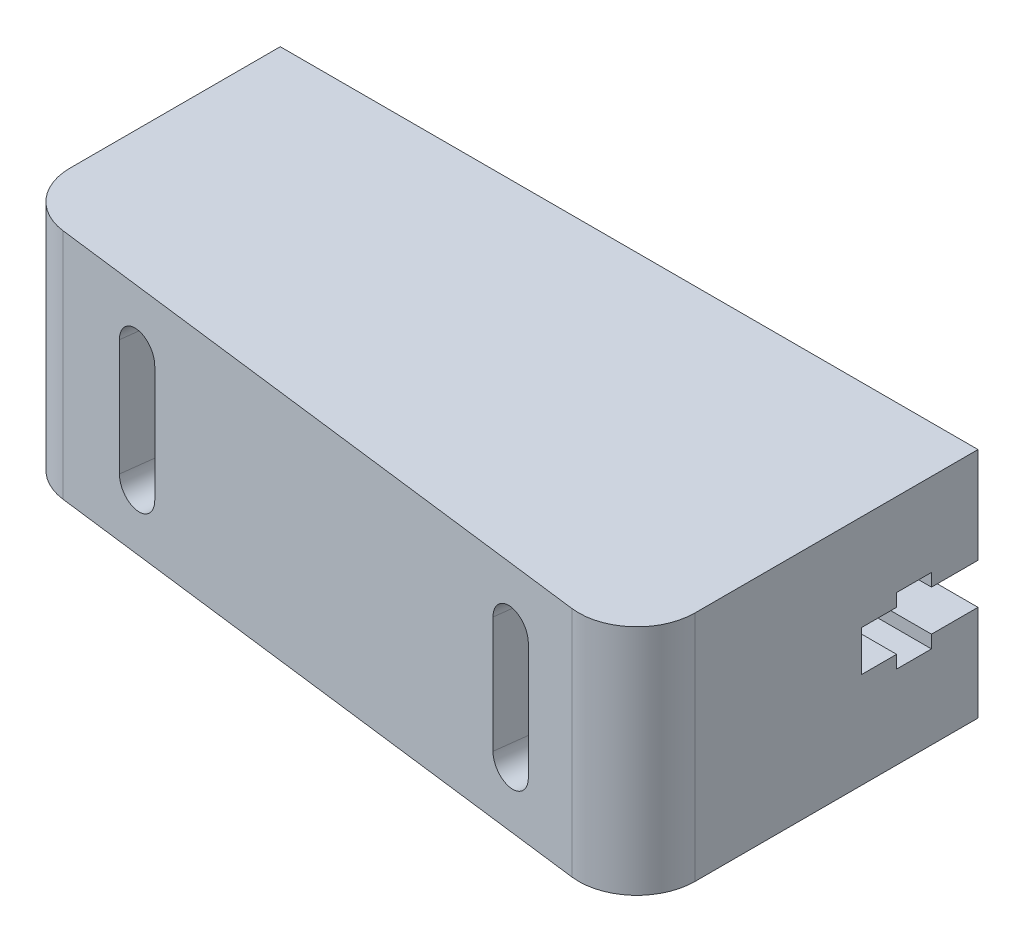
SolidWorks part; units mm, degrees
ref_plane "Front Plane" through (0, 0, 0) normal (0, 0, 1) x (1, 0, 0)
ref_plane "Top Plane" through (0, 0, 0) normal (0, 1, 0) x (1, 0, 0)
ref_plane "Right Plane" through (0, 0, 0) normal (1, 0, 0) x (0, 0, -1)
sketch "Sketch1" plane through (0, 0, 0) normal (0, 0, 1) x (1, 0, 0)
  line L1 (-30, 10) -> (30, 10)
  line L2 (-30, 10) -> (-30, -10)
  line L3 (-30, -10) -> (30, -10)
  line L4 (30, 10) -> (30, -10)
  line L5 (-30, 10) -> (30, -10) construction
  line L6 (-30, -10) -> (30, 10) construction
  point P0 (0, 0)
  dimension "D1" = 60
  dimension "D2" = 20
extrude "Boss-Extrude1" add sketch "Sketch1" along normal blind 30
sketch "Sketch2" plane through (0, 10, 0) normal (0, 1, 0) x (1, 0, 0)
  line L0 (-30, -30) -> (30, -30)
  line L1 (30, -30) -> (-30, -22.5)
  line L2 (-30, -30) -> (-30, 0) construction
  line L3 (-30, -22.5) -> (-30, -30)
  dimension "D1" = 7.5
extrude "Cut-Extrude1" cut sketch "Sketch2" against normal through all
sketch "Sketch3" plane through (0, 10, 0) normal (0, 1, 0) x (1, 0, 0)
  line L16 (-25, 0) -> (25, 0)
  line L19 (25, 0) -> (25, -24.3361)
  line L20 (25, -24.3361) -> (-25, -18.0861)
  line L21 (-25, -18.0861) -> (-25, 0)
  line L22 (25, 0) -> (25, -24.3361)
  line L23 (25, -24.3361) -> (-25, -18.0861)
  line L24 (-25, -18.0861) -> (-25, 0)
  dimension "D1" = 5
extrude "Cut-Extrude2" cut sketch "Sketch3" against normal through all from offset 4 offset against normal yes
sketch "Sketch4" plane through (-30, 0, 0) normal (-1, 0, 0) x (0, 0, 1)
  line L0 (0, 0) -> (22.5, 0) construction
  line L1 (22.5, -10) -> (22.5, 10) construction
  line L2 (0, 1.75) -> (4, 1.75)
  line L3 (0, 10) -> (0, -10) construction
  line L4 (4, 1.75) -> (4, 2.85)
  line L5 (4, 2.85) -> (7, 2.85)
  line L6 (7, 2.85) -> (7, 1.75)
  line L7 (7, 1.75) -> (10, 1.75)
  line L8 (10, 1.75) -> (10, -1.75)
  line L9 (7, -1.75) -> (10, -1.75)
  line L10 (7, -2.85) -> (7, -1.75)
  line L11 (4, -2.85) -> (7, -2.85)
  line L12 (4, -1.75) -> (4, -2.85)
  line L13 (0, -1.75) -> (4, -1.75)
  point P17 (10, 0)
  dimension "D1" = 3.5
  dimension "D2" = 5.7
  dimension "D3" = 10
  dimension "D4" = 3
  dimension "D5" = 4
extrude "Cut-Extrude3" cut sketch "Sketch4" against normal through all and the other way through all
sketch "Sketch5" plane through (-3.2308, 0, 25.8462) normal (-0.124, 0, 0.9923) x (0.9923, 0, 0.124)
  line L0 (-15.2441, 0) -> (21.7559, 0) construction
  line L1 (33.4894, 10) -> (-26.9776, 10) construction
  line L2 (-26.9776, -10) -> (-26.9776, 10) construction
  circle A0 centre (21.7559, 0) radius 1.75
  circle A1 centre (-15.2441, 0) radius 1.75
  point P6 (3.2559, 0)
  point P9 (3.2559, 10)
  point P12 (-26.9776, 0)
  dimension "D1" = 3.5
  dimension "D2" = 37
extrude "Cut-Extrude4" cut sketch "Sketch5" against normal through all
sketch "Sketch6" plane through (-3.2308, 0, 25.8462) normal (-0.124, 0, 0.9923) x (0.9923, 0, 0.124)
  line L0 (-15.2441, 5) -> (-15.2441, -5) construction
  line L1 (-13.4941, 5) -> (-13.4941, -5)
  line L2 (-16.9941, 5) -> (-16.9941, -5)
  line L3 (3.2559, 10) -> (3.2559, -10) construction
  line L4 (33.4894, 10) -> (-26.9776, 10) construction
  line L5 (33.4894, -10) -> (-26.9776, -10) construction
  line L6 (21.7559, 5) -> (21.7559, -5) construction
  line L7 (20.0059, 5) -> (20.0059, -5)
  line L8 (23.5059, 5) -> (23.5059, -5)
  arc A0 (-13.4941, 5) -> (-16.9941, 5) centre (-15.2441, 5) ccw
  arc A1 (-16.9941, -5) -> (-13.4941, -5) centre (-15.2441, -5) ccw
  circle A2 centre (-15.2441, 0) radius 1.75 construction
  arc A3 (20.0059, 5) -> (23.5059, 5) centre (21.7559, 5) cw
  arc A4 (23.5059, -5) -> (20.0059, -5) centre (21.7559, -5) cw
  point P2 (-15.2441, 0)
  point P17 (21.7559, 0)
  dimension "D1" = 10
extrude "Cut-Extrude5" cut sketch "Sketch6" against normal up to surface (5 mm away) up to face at (20.7138, 0, 23.8003)
fillet "Fillet1" radius 5 2 edges at (30, 0, 30) (-30, 0, 22.5)
